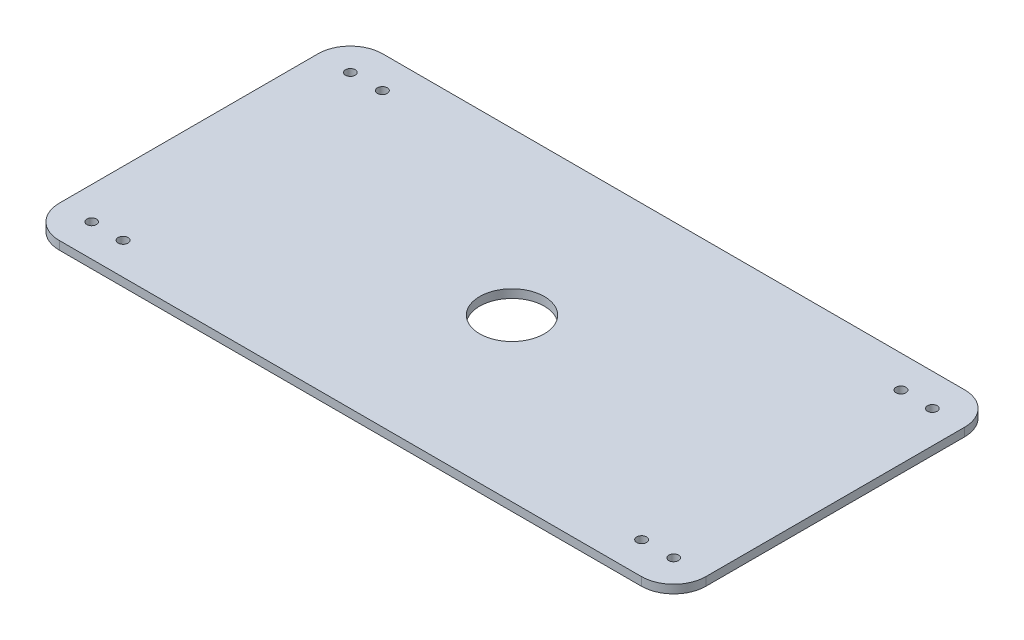
SolidWorks part; units mm, degrees
ref_plane "Front Plane" through (0, 0, 0) normal (0, 0, 1) x (1, 0, 0)
ref_plane "Top Plane" through (0, 0, 0) normal (0, 1, 0) x (1, 0, 0)
ref_plane "Right Plane" through (0, 0, 0) normal (1, 0, 0) x (0, 0, -1)
sketch "Sketch1" plane through (0, 0, 0) normal (0, 1, 0) x (1, 0, 0)
  line L1 (0, 0) -> (200, 0)
  line L2 (0, 0) -> (0, -100)
  line L3 (0, -100) -> (200, -100)
  line L4 (200, 0) -> (200, -100)
  dimension "D1" = 100
  dimension "D2" = 200
extrude "Boss-Extrude1" add sketch "Sketch1" along normal blind 2.6 contours L1 L4 L3 L2
fillet "Fillet1" radius 10 4 edges at (0, 1.3, 0) (0, 1.3, 100) (200, 1.3, 100) (200, 1.3, 0)
sketch "Sketch6" plane through (0, 0, 0) normal (0, -1, 0) x (1, 0, 0)
  line L0 (200, 10) -> (200, 90) construction
  line L1 (10, 0) -> (190, 0) construction
  circle A0 centre (190, 10) radius 1.5
  dimension "D1" = 3
  dimension "D2" = 10
  dimension "D3" = 10
ref_plane "Plane1" through (100, 0, 0) normal (1, 0, 0) x (0, 0, -1)
extrude "Cut-Extrude6" cut sketch "Sketch6" against normal blind 2.6 contours A0
ref_plane "Plane14" through (0, 0, 50) normal (0, 0, 1) x (1, 0, 0)
mirror "Mirror5" about plane through (100, 0, 0) normal (1, 0, 0) of "Cut-Extrude6"
mirror "Mirror6" about plane through (0, 0, 50) normal (0, 0, 1) of "Mirror5", "Cut-Extrude6"
sketch "Sketch15" plane through (0, 0, 0) normal (0, -1, 0) x (1, 0, 0)
  line L0 (100, 0) -> (100, 100) construction
  line L2 (0, 50) -> (200, 50) construction
  line L4 (0, 10) -> (0, 90) construction
  line L5 (200, 10) -> (200, 90) construction
  line L6 (10, 0) -> (190, 0) construction
  line L7 (10, 100) -> (190, 100) construction
  circle A0 centre (100, 50) radius 10
  dimension "D1" = 20
extrude "Cut-Extrude14" cut sketch "Sketch15" against normal through all contours A0
sketch "Sketch23" plane through (0, 2.6, 0) normal (0, 1, 0) x (1, 0, 0)
  circle A0 centre (19.812, -9.906) radius 1.524
extrude "Cut-Extrude16" cut sketch "Sketch23" against normal blind 2.6
mirror "Mirror7" about plane through (100, 0, 0) normal (1, 0, 0) of "Cut-Extrude16"
mirror "Mirror8" about plane through (0, 0, 50) normal (0, 0, 1) of "Mirror7", "Cut-Extrude16"
